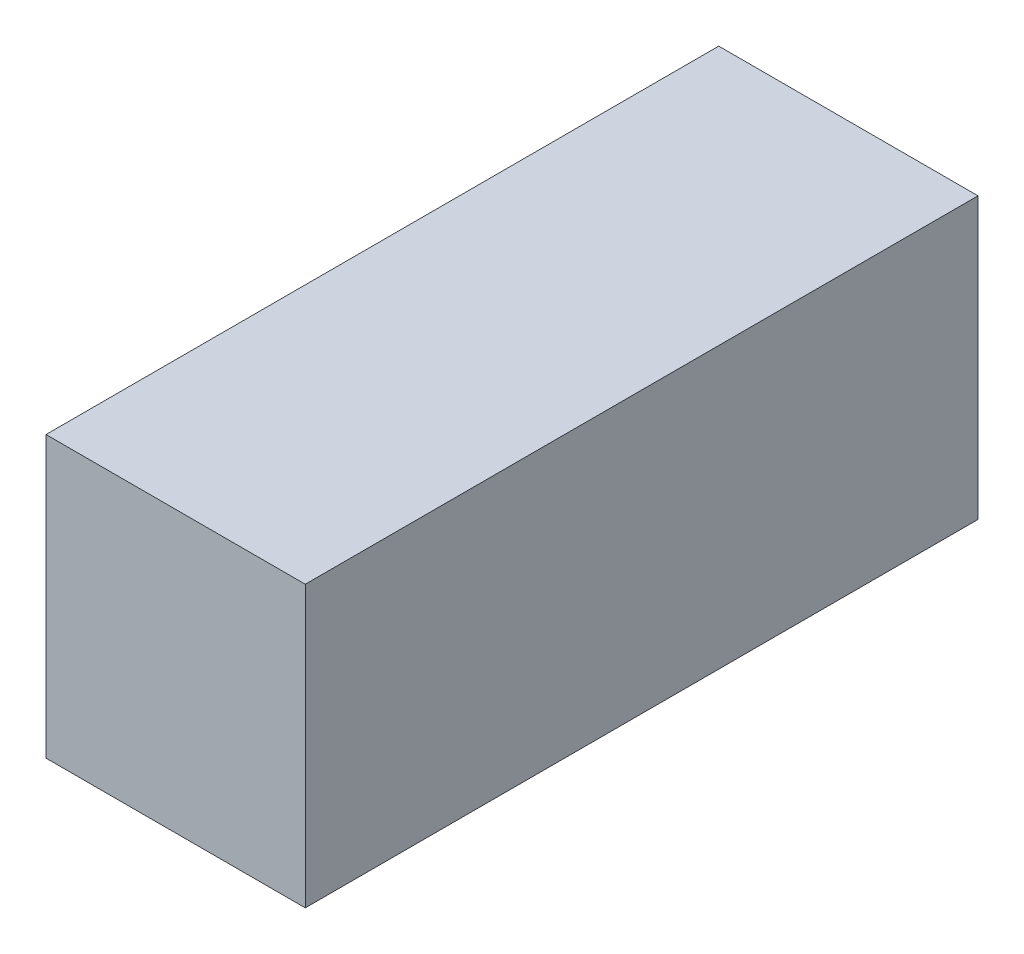
SolidWorks part; units mm, degrees
ref_plane "Front Plane" through (0, 0, 0) normal (0, 0, 1) x (1, 0, 0)
ref_plane "Top Plane" through (0, 0, 0) normal (0, 1, 0) x (1, 0, 0)
ref_plane "Right Plane" through (0, 0, 0) normal (1, 0, 0) x (0, 0, -1)
sketch "Sketch1" plane through (0, 0, 0) normal (0, 0, 1) x (1, 0, 0)
  line L1 (0, 0) -> (185, 0)
  line L2 (0, 0) -> (0, 200)
  line L3 (0, 200) -> (185, 200)
  line L4 (185, 0) -> (185, 200)
  dimension "D1" = 200
  dimension "D2" = 185
extrude "Boss-Extrude1" add sketch "Sketch1" along normal blind 480
